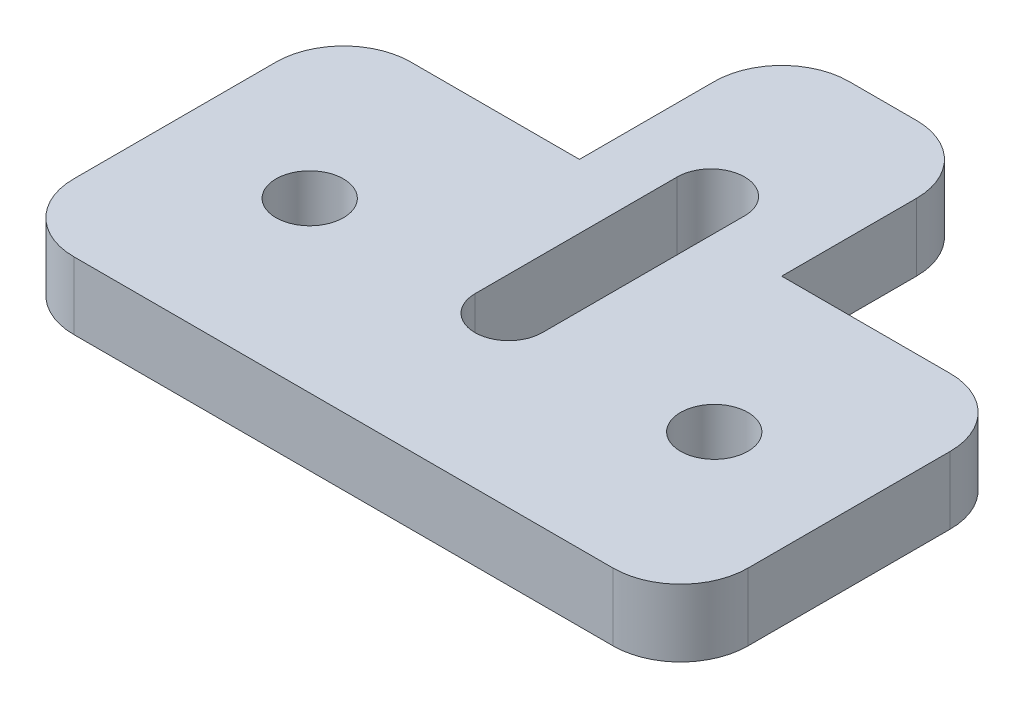
SolidWorks part; units mm, degrees
ref_plane "Front Plane" through (0, 0, 0) normal (0, 0, 1) x (1, 0, 0)
ref_plane "Top Plane" through (0, 0, 0) normal (0, 1, 0) x (1, 0, 0)
ref_plane "Right Plane" through (0, 0, 0) normal (1, 0, 0) x (0, 0, -1)
sketch "Sketch1" plane through (0, 0, 0) normal (0, 1, 0) x (1, 0, 0)
  line L0 (0, 0) -> (-130, 0)
  line L2 (0, 0) -> (0, 50)
  line L3 (-130, 0) -> (-130, 50)
  line L4 (-130, 50) -> (-80, 50)
  line L5 (0, 50) -> (-50, 50)
  line L6 (-50, 50) -> (-50, 80)
  line L7 (-50, 80) -> (-80, 80)
  line L8 (-80, 80) -> (-80, 50)
extrude "Boss-Extrude1" add sketch "Sketch1" along normal blind 10
sketch "Sketch2" plane through (0, 10, 0) normal (0, 1, 0) x (1, 0, 0)
  line L1 (0, 0) -> (0, 50) construction
  circle A0 centre (-95, 25) radius 5
  circle A1 centre (-35, 25) radius 5
extrude "Cut-Extrude1" cut sketch "Sketch2" against normal blind 26
fillet "Fillet4" radius 10 2 edges at (-80, 5, -80) (-130, 5, -50)
fillet "Fillet5" radius 10 1 edges at (-50, 5, -80)
fillet "Fillet6" radius 10 1 edges at (0, 5, -50)
fillet "Fillet7" radius 10 1 edges at (0, 5, 0)
sketch "Sketch3" plane through (0, 10, 0) normal (0, 1, 0) x (1, 0, 0)
  line L0 (-10, 50) -> (-50, 50) construction
  line L5 (-70.4933, 55) -> (-70.4933, 25)
  line L7 (-60.4933, 55) -> (-60.4933, 25)
  arc A0 (-60.4933, 55) -> (-70.4933, 55) centre (-65.4933, 55) ccw
  arc A1 (-70.4933, 25) -> (-60.4933, 25) centre (-65.4933, 25) ccw
  dimension "D1" = 5
  dimension "D2" = 10
extrude "Cut-Extrude2" cut sketch "Sketch3" against normal blind 26
fillet "Fillet9" radius 10 1 edges at (-130, 5, 0)
sketch "Sketch5" plane through (0, 10, 0) normal (0, 1, 0) x (1, 0, 0)
  line L0 (-115, 50) -> (-115, 0)
  line L1 (-80, 50) -> (-120, 50) construction
  line L2 (-120, 0) -> (-10, 0) construction
  line L3 (-115, 0) -> (-115, 50)
  line L4 (-130, 40) -> (-130, 10) construction
  line L6 (-15, 50) -> (-15, 0)
  line L7 (-10, 50) -> (-50, 50) construction
  line L8 (-15, 0) -> (-15, 50)
  line L9 (0, 10) -> (0, 40) construction
  line M7 (-130, 40) -> (-130, 10)
  arc M8 (-130, 10) -> (-120, 0) centre (-120, 10) ccw
  line M9 (-120, 0) -> (-10, 0)
  line M19 (-80, 50) -> (-120, 50)
  arc M20 (-120, 50) -> (-130, 40) centre (-120, 40) ccw
  dimension "D1" = 15
  dimension "D2" = 15
extrude "Cut-Extrude3" cut sketch "Sketch5" against normal blind 31 contours L0 M19 M20 M7 M8 M9
sketch "Sketch6" plane through (0, 10, 0) normal (0, 1, 0) x (1, 0, 0)
  line L0 (-15, 50) -> (-15, 0)
  line L1 (-10, 50) -> (-50, 50) construction
  line L2 (-115, 0) -> (-10, 0) construction
  line L3 (-15, 0) -> (-15, 50)
  line L4 (0, 10) -> (0, 40) construction
  line M9 (-115, 0) -> (-10, 0)
  arc M10 (-10, 0) -> (0, 10) centre (-10, 10) ccw
  line M11 (0, 10) -> (0, 40)
  arc M12 (0, 40) -> (-10, 50) centre (-10, 40) ccw
  line M13 (-10, 50) -> (-50, 50)
  dimension "D1" = 15
extrude "Cut-Extrude5" cut sketch "Sketch6" against normal blind 32 contours L0 M13 M9 M10 M11 M12
fillet "Fillet10" radius 10 1 edges at (-15, 5, -50)
fillet "Fillet11" radius 10 1 edges at (-115, 5, -50)
fillet "Fillet12" radius 10 1 edges at (-15, 5, 0)
fillet "Fillet13" radius 10 1 edges at (-115, 5, 0)
